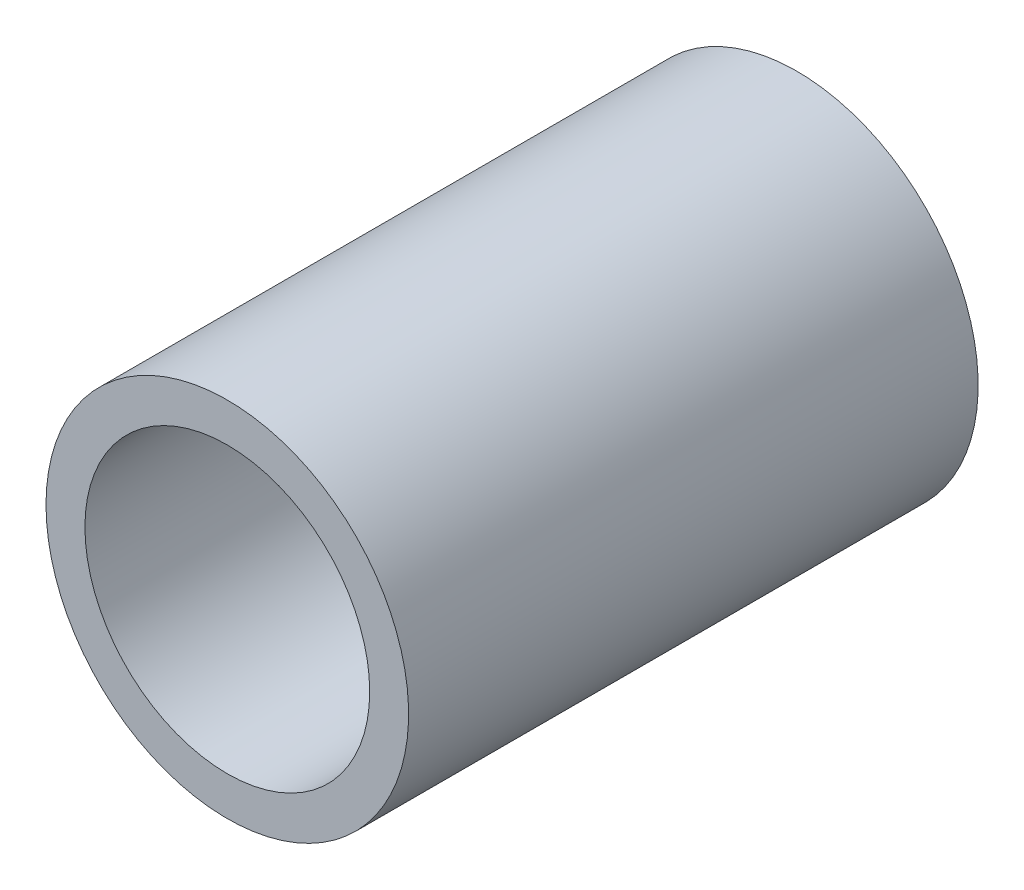
SolidWorks part; units mm, degrees
ref_plane "Front Plane" through (0, 0, 0) normal (0, 0, 1) x (1, 0, 0)
ref_plane "Top Plane" through (0, 0, 0) normal (0, 1, 0) x (1, 0, 0)
ref_plane "Right Plane" through (0, 0, 0) normal (1, 0, 0) x (0, 0, -1)
sketch "Sketch1" plane through (0, 0, 0) normal (0, 0, 1) x (1, 0, 0)
  circle A0 centre (0, 0) radius 24.257
  circle A1 centre (0, 0) radius 19.05
  dimension "D1" = 38.1
  dimension "D2" = 48.514
extrude "Boss-Extrude1" add sketch "Sketch1" along normal blind 76.2
equation "\"D2@Sketch1\"=1.91"
